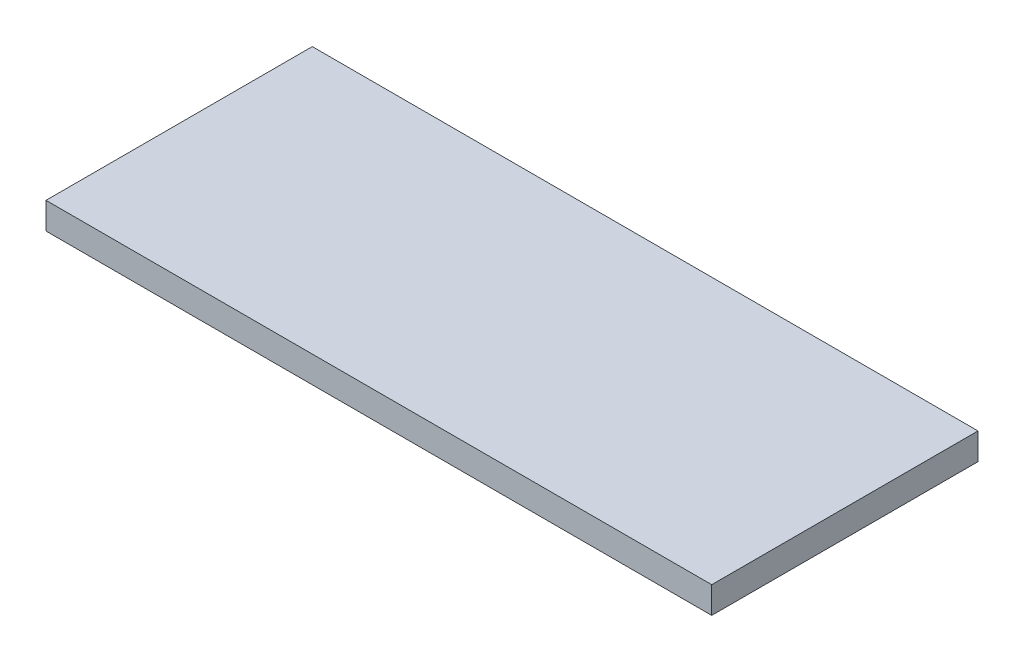
SolidWorks part; units mm, degrees
ref_plane "Front Plane" through (0, 0, 0) normal (0, 0, 1) x (1, 0, 0)
ref_plane "Top Plane" through (0, 0, 0) normal (0, 1, 0) x (1, 0, 0)
ref_plane "Right Plane" through (0, 0, 0) normal (1, 0, 0) x (0, 0, -1)
sketch "Sketch1" plane through (0, 0, 0) normal (0, 1, 0) x (1, 0, 0)
  line L1 (-2500, -1000) -> (2500, -1000)
  line L2 (-2500, -1000) -> (-2500, 1000)
  line L3 (-2500, 1000) -> (2500, 1000)
  line L4 (2500, -1000) -> (2500, 1000)
  line L5 (-2500, -1000) -> (2500, 1000) construction
  line L6 (-2500, 1000) -> (2500, -1000) construction
  point P0 (0, 0)
  dimension "D1" = 5000
  dimension "D2" = 2000
extrude "Boss-Extrude3" add sketch "Sketch1" along normal blind 200
